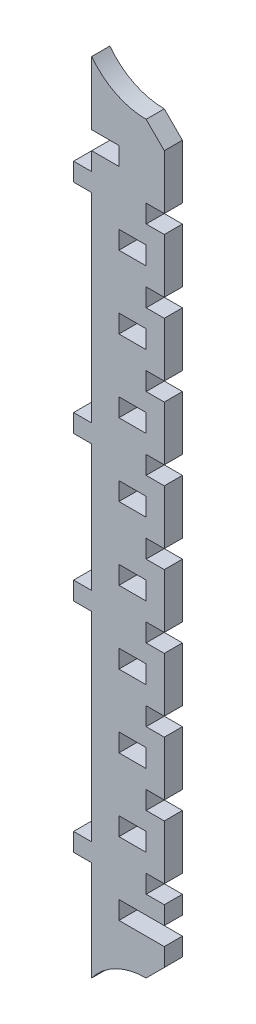
SolidWorks part; units mm, degrees
ref_plane "Front Plane" through (0, 0, 0) normal (0, 0, 1) x (1, 0, 0)
ref_plane "Top Plane" through (0, 0, 0) normal (0, 1, 0) x (1, 0, 0)
ref_plane "Right Plane" through (0, 0, 0) normal (1, 0, 0) x (0, 0, -1)
sketch "Sketch1" plane through (0, 0, 0) normal (0, 0, 1) x (1, 0, 0)
  line L892 (18, 157.5) -> (15, 157.5)
  line L893 (15, 157.5) -> (15, 154.5)
  line L894 (15, 154.5) -> (18, 154.5)
  line L895 (18, 154.5) -> (18, 145.5)
  line L896 (18, 145.5) -> (15, 145.5)
  line L897 (15, 145.5) -> (15, 142.5)
  line L898 (15, 142.5) -> (18, 142.5)
  line L899 (18, 142.5) -> (18, 133.5)
  line L900 (18, 133.5) -> (15, 133.5)
  line L901 (15, 133.5) -> (15, 130.5)
  line L902 (15, 130.5) -> (18, 130.5)
  line L903 (18, 130.5) -> (18, 121.5)
  line L904 (18, 121.5) -> (15, 121.5)
  line L905 (15, 121.5) -> (15, 118.5)
  line L906 (15, 118.5) -> (18, 118.5)
  line L907 (18, 118.5) -> (18, 109.5)
  line L908 (18, 109.5) -> (15, 109.5)
  line L909 (15, 109.5) -> (15, 106.5)
  line L910 (15, 106.5) -> (18, 106.5)
  line L911 (18, 106.5) -> (18, 97.5)
  line L912 (18, 97.5) -> (15, 97.5)
  line L913 (15, 97.5) -> (15, 94.5)
  line L914 (15, 94.5) -> (18, 94.5)
  line L915 (18, 94.5) -> (18, 85.5)
  line L916 (18, 85.5) -> (15, 85.5)
  line L917 (15, 85.5) -> (15, 82.5)
  line L918 (15, 82.5) -> (18, 82.5)
  line L919 (18, 82.5) -> (18, 73.5)
  line L920 (18, 73.5) -> (15, 73.5)
  line L921 (15, 73.5) -> (15, 70.5)
  line L922 (15, 70.5) -> (18, 70.5)
  line L923 (18, 70.5) -> (18, 67.5)
  line L924 (18, 67.5) -> (10.5, 67.5)
  line L925 (10.5, 67.5) -> (10.5, 64.5)
  line L926 (10.5, 64.5) -> (18, 64.5)
  line L927 (18, 64.5) -> (18, 61.5)
  line L928 (18, 61.5) -> (15, 58.5)
  line L929 (6, 54) -> (6, 70.5)
  line L930 (6, 70.5) -> (3, 70.5)
  line L931 (3, 70.5) -> (3, 73.5)
  line L932 (3, 73.5) -> (6, 73.5)
  line L933 (6, 73.5) -> (6, 106.5)
  line L934 (6, 106.5) -> (3, 106.5)
  line L935 (3, 106.5) -> (3, 109.5)
  line L936 (3, 109.5) -> (6, 109.5)
  line L937 (6, 109.5) -> (6, 130.5)
  line L938 (6, 130.5) -> (3, 130.5)
  line L939 (3, 130.5) -> (3, 133.5)
  line L940 (3, 133.5) -> (6, 133.5)
  line L941 (6, 133.5) -> (6, 166.5)
  line L942 (6, 166.5) -> (3, 166.5)
  line L943 (3, 166.5) -> (3, 169.5)
  line L944 (3, 169.5) -> (6, 169.5)
  line L945 (6, 169.5) -> (6, 172.5)
  line L946 (6, 172.5) -> (10.5, 172.5)
  line L947 (10.5, 172.5) -> (10.5, 175.5)
  line L948 (10.5, 175.5) -> (6, 175.5)
  line L949 (6, 175.5) -> (6, 186)
  line L950 (15, 181.5) -> (18, 178.5)
  line L951 (18, 178.5) -> (18, 169.5)
  line L952 (18, 169.5) -> (15, 169.5)
  line L953 (15, 169.5) -> (15, 166.5)
  line L954 (15, 166.5) -> (18, 166.5)
  line L955 (18, 166.5) -> (18, 157.5)
  line L956 (15, 79.5) -> (10.5, 79.5)
  line L957 (10.5, 79.5) -> (10.5, 76.5)
  line L958 (10.5, 76.5) -> (15, 76.5)
  line L959 (15, 76.5) -> (15, 79.5)
  line L960 (15, 163.5) -> (10.5, 163.5)
  line L961 (10.5, 163.5) -> (10.5, 160.5)
  line L962 (10.5, 160.5) -> (15, 160.5)
  line L963 (15, 160.5) -> (15, 163.5)
  line L964 (15, 151.5) -> (10.5, 151.5)
  line L965 (10.5, 151.5) -> (10.5, 148.5)
  line L966 (10.5, 148.5) -> (15, 148.5)
  line L967 (15, 148.5) -> (15, 151.5)
  line L968 (15, 139.5) -> (10.5, 139.5)
  line L969 (10.5, 139.5) -> (10.5, 136.5)
  line L970 (10.5, 136.5) -> (15, 136.5)
  line L971 (15, 136.5) -> (15, 139.5)
  line L972 (15, 127.5) -> (10.5, 127.5)
  line L973 (10.5, 127.5) -> (10.5, 124.5)
  line L974 (10.5, 124.5) -> (15, 124.5)
  line L975 (15, 124.5) -> (15, 127.5)
  line L976 (15, 115.5) -> (10.5, 115.5)
  line L977 (10.5, 115.5) -> (10.5, 112.5)
  line L978 (10.5, 112.5) -> (15, 112.5)
  line L979 (15, 112.5) -> (15, 115.5)
  line L980 (15, 103.5) -> (10.5, 103.5)
  line L981 (10.5, 103.5) -> (10.5, 100.5)
  line L982 (10.5, 100.5) -> (15, 100.5)
  line L983 (15, 100.5) -> (15, 103.5)
  line L984 (15, 91.5) -> (10.5, 91.5)
  line L985 (10.5, 91.5) -> (10.5, 88.5)
  line L986 (10.5, 88.5) -> (15, 88.5)
  line L987 (15, 88.5) -> (15, 91.5)
  arc A14 (15, 58.5) -> (6, 54) centre (15, 47.25) ccw
  arc A15 (6, 186) -> (15, 181.5) centre (15, 192.75) ccw
extrude "Boss-Extrude1" add sketch "Sketch1" along normal blind 3
